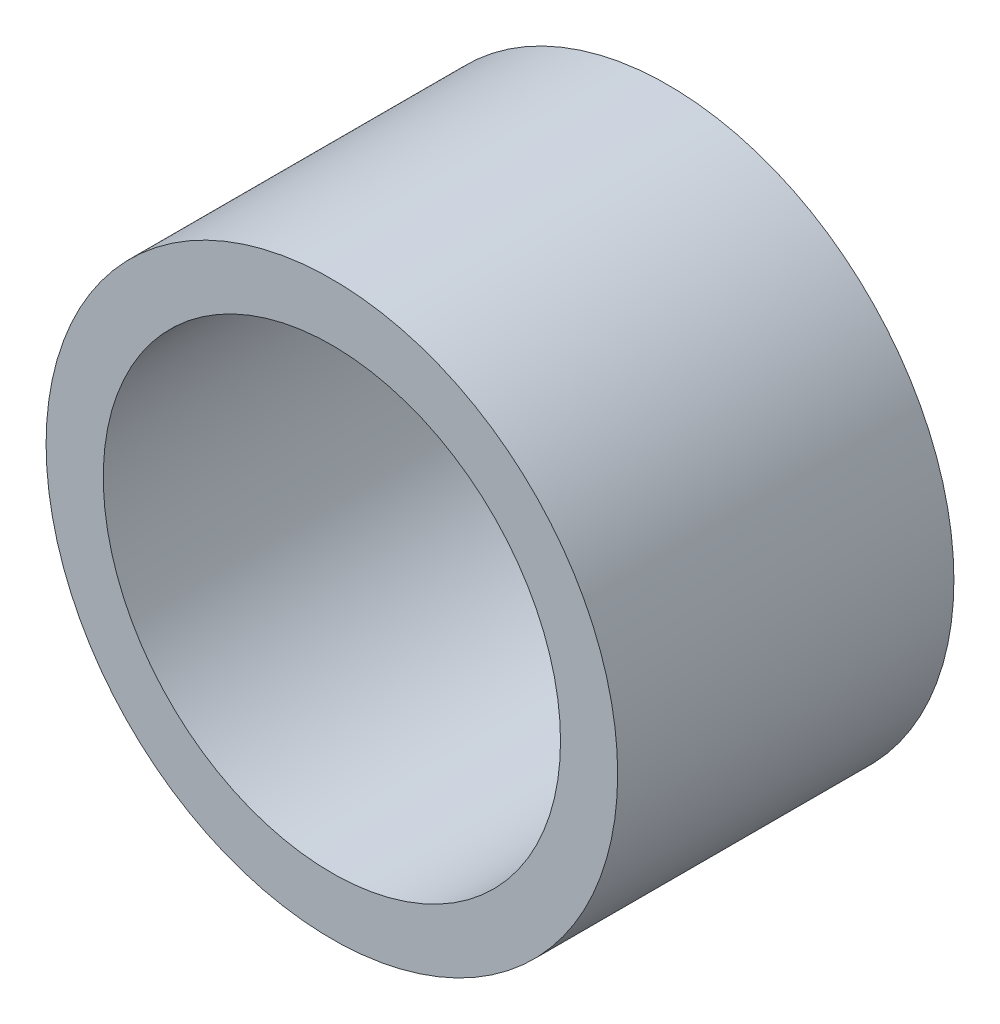
SolidWorks part; units mm, degrees
ref_plane "Front Plane" through (0, 0, 0) normal (0, 0, 1) x (1, 0, 0)
ref_plane "Top Plane" through (0, 0, 0) normal (0, 1, 0) x (1, 0, 0)
ref_plane "Right Plane" through (0, 0, 0) normal (1, 0, 0) x (0, 0, -1)
sketch "Sketch1" plane through (0, 0, 0) normal (0, 0, 1) x (1, 0, 0)
  circle A0 centre (0, 0) radius 4.25
  circle A1 centre (0, 0) radius 3.4
  dimension "D1" = 6.8
  dimension "D2" = 8.5
extrude "Boss-Extrude1" add sketch "Sketch1" along normal blind 5
